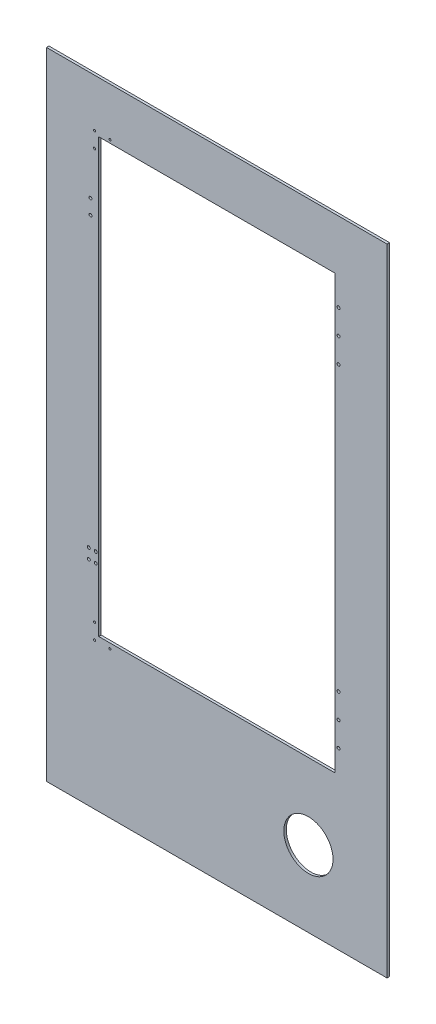
SolidWorks part; units mm, degrees
material "PE High Density"
ref_plane "Front Plane" through (0, 0, 0) normal (0, 0, 1) x (1, 0, 0)
ref_plane "Top Plane" through (0, 0, 0) normal (0, 1, 0) x (1, 0, 0)
ref_plane "Right Plane" through (0, 0, 0) normal (1, 0, 0) x (0, 0, -1)
sketch "Sketch1" plane through (0, 0, 0) normal (0, 0, 1) x (1, 0, 0)
  line L9 (0, 0) -> (879.7036, 0)
  line L12 (0, -1641.475) -> (879.7036, -1641.475)
  line L17 (0, 0) -> (0, -1641.475)
  line L18 (879.7036, 0) -> (879.7036, -1641.475)
  dimension "D2" = 879.7036
  dimension "D3" = 1641.475
extrude "Boss-Extrude1" add sketch "Sketch1" along normal blind 6.35
fillet "Fillet1" radius 0.254 4 edges at (879.7036, -1641.475, 3.175) (0, -1641.475, 3.175) (0, 0, 3.175) (879.7036, 0, 3.175)
sketch "Sketch2" plane through (0, 0, 6.35) normal (0, 0, 1) x (1, 0, 0)
  line L0 (879.4496, 0) -> (0.254, 0) construction
  line L1 (135.0518, -132.334) -> (744.6518, -132.334)
  line L2 (135.0518, -132.334) -> (135.0518, -1249.934)
  line L3 (135.0518, -1249.934) -> (744.6518, -1249.934)
  line L4 (744.6518, -132.334) -> (744.6518, -1249.934)
  point P6 (439.8518, 0)
  point P7 (439.8518, -132.334)
  dimension "D1" = 609.6
  dimension "D2" = 1117.6
  dimension "D3" = 132.334
extrude "Cut-Extrude1" cut sketch "Sketch2" against normal through all
sketch "Sketch3" plane through (0, 0, 6.35) normal (0, 0, 1) x (1, 0, 0)
  line L0 (744.6518, -1249.934) -> (744.6518, -132.334) construction
  line L1 (135.0518, -1249.934) -> (744.6518, -1249.934) construction
  line L2 (744.6518, -132.334) -> (135.0518, -132.334) construction
  line L3 (135.0518, -132.334) -> (135.0518, -1249.934) construction
  line L4 (879.4496, 0) -> (0.254, 0) construction
  circle A0 centre (754.3546, -204.724) radius 3.81
  circle A1 centre (754.3546, -268.224) radius 3.81
  circle A2 centre (754.3546, -331.724) radius 3.81
  circle A3 centre (754.3546, -1190.244) radius 3.81
  circle A4 centre (754.3546, -1126.744) radius 3.81
  circle A5 centre (754.3546, -1063.244) radius 3.81
  circle A6 centre (109.383, -1063.863) radius 3.81
  circle A7 centre (127.3831, -1063.863) radius 3.81
  circle A8 centre (127.3831, -1089.863) radius 3.81
  circle A9 centre (109.383, -1089.863) radius 3.81
  circle A10 centre (113.7484, -280.289) radius 3.81
  circle A11 centre (113.7484, -318.389) radius 3.81
  dimension "D2" = 7.62
  dimension "D9" = 7.62
  dimension "D17" = 7.62
  dimension "D1" = 9.7028
  dimension "D3" = 59.69
  dimension "D4" = 63.5
  dimension "D5" = 63.5
  dimension "D6" = 72.39
  dimension "D7" = 63.5
  dimension "D8" = 63.5
  dimension "D10" = 18
  dimension "D11" = 26
  dimension "D12" = 7.6687
  dimension "D13" = 160.071
  dimension "D14" = 38.1
  dimension "D15" = 21.3034
  dimension "D16" = 280.289
extrude "Cut-Extrude2" cut sketch "Sketch3" against normal through all
sketch "Sketch5" plane through (0, 0, 6.35) normal (0, 0, 1) x (1, 0, 0)
  line L0 (676.5036, -1249.934) -> (676.5036, -1641.475) construction
  line L5 (135.0518, -1249.934) -> (744.6518, -1249.934) construction
  line L6 (879.7036, -1641.221) -> (879.7036, -0.254) construction
  line L8 (0.254, -1641.475) -> (879.4496, -1641.475) construction
  circle A0 centre (676.5036, -1445.7045) radius 63.5
  point P11 (676.5036, -1445.7045)
  dimension "D1" = 127
  dimension "D2" = 203.2
extrude "Cut-Extrude4" cut sketch "Sketch5" against normal through all
sketch "Sketch6" plane through (0, 0, 0) normal (0, 0, -1) x (-1, 0, 0)
  line L0 (-124.3, -1223.551) -> (-124.3, -1263.175) construction
  line L1 (-124.3, -1263.175) -> (-163.924, -1263.175) construction
  line L2 (-135.0518, -132.334) -> (-135.0518, -1249.934) construction
  line L3 (-135.0518, -1249.934) -> (-744.6518, -1249.934) construction
  line L4 (-135.0518, -691.134) -> (0, -691.134) construction
  line L5 (0, -0.254) -> (0, -1641.221) construction
  line L6 (-124.3, -124.3) -> (-163.924, -124.3) construction
  line L7 (-124.3, -163.924) -> (-124.3, -124.3) construction
  line L9 (-744.6518, -132.334) -> (-135.0518, -132.334) construction
  circle A0 centre (-124.3, -1223.551) radius 2.7
  circle A1 centre (-124.3, -1263.175) radius 2.7
  circle A2 centre (-163.924, -1263.175) radius 2.7
  circle A3 centre (-163.924, -124.3) radius 2.7
  circle A4 centre (-124.3, -124.3) radius 2.7
  circle A5 centre (-124.3, -163.924) radius 2.7
  dimension "D1" = 5.4
  dimension "D6" = 5.4
  dimension "D2" = 10.7518
  dimension "D3" = 13.241
  dimension "D4" = 39.624
  dimension "D5" = 39.624
  dimension "D7" = 10.7518
  dimension "D8" = 8.034
extrude "Cut-Extrude5" cut sketch "Sketch6" against normal through all
